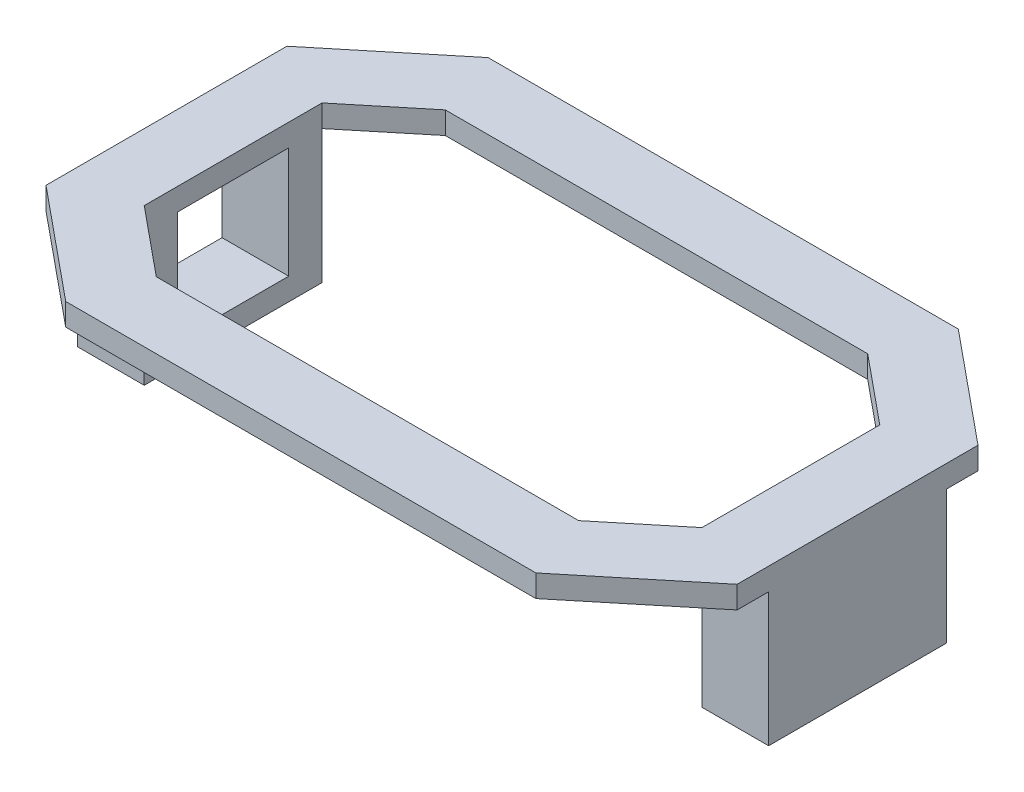
SolidWorks part; units mm, degrees
ref_plane "Front Plane" through (0, 0, 0) normal (0, 0, 1) x (1, 0, 0)
ref_plane "Top Plane" through (0, 0, 0) normal (0, 1, 0) x (1, 0, 0)
ref_plane "Right Plane" through (0, 0, 0) normal (1, 0, 0) x (0, 0, -1)
sketch "Sketch1" plane through (0, 0, 0) normal (0, 1, 0) x (1, 0, 0)
  line L0 (15, 0) -> (140.43, 0) construction
  line L1 (0, 0) -> (15, 0)
  line L2 (0, 0) -> (0, 40)
  line L3 (0, 40) -> (15, 40)
  line L4 (15, 0) -> (15, 40)
  line L5 (0, 0) -> (15, 40) construction
  line L6 (0, 40) -> (15, 0) construction
  line L7 (147.93, 0) -> (147.93, 40) construction
  line L8 (140.43, 0) -> (155.43, 0)
  line L9 (140.43, 0) -> (140.43, 40)
  line L10 (140.43, 40) -> (155.43, 40)
  line L11 (155.43, 0) -> (155.43, 40)
  line L12 (140.43, 0) -> (155.43, 40) construction
  line L13 (140.43, 40) -> (155.43, 0) construction
  line L14 (140.43, 20) -> (155.43, 20) construction
  line L15 (77.715, 0) -> (77.715, 21.3226) construction
  circle A0 centre (144.18, 5) radius 2
  circle A1 centre (151.68, 5) radius 2
  circle A2 centre (151.68, 35) radius 2
  circle A3 centre (144.18, 35) radius 2
  circle A4 centre (3.75, 35) radius 2
  circle A5 centre (11.25, 35) radius 2
  circle A6 centre (11.25, 5) radius 2
  circle A7 centre (3.75, 5) radius 2
  point P4 (7.5, 20)
  point P10 (147.93, 20)
  dimension "D6" = 4
  dimension "D1" = 40
  dimension "D2" = 15
  dimension "D3" = 125.43
  dimension "D4" = 40
  dimension "D5" = 15
  dimension "D7" = 3.75
  dimension "D8" = 5
extrude "Boss-Extrude1" add sketch "Sketch1" along normal blind 30
sketch "Sketch2" plane through (0, 30, 0) normal (0, 1, 0) x (1, 0, 0)
  line L0 (15, 20) -> (140.43, 20) construction
  line L1 (15, 0) -> (15, 40) construction
  line L2 (140.43, 40) -> (140.43, 0) construction
  line L3 (15, 40) -> (30.215, 52.5)
  line L4 (30.215, -12.5) -> (125.215, -12.5) construction
  line L5 (30.215, -12.5) -> (30.215, 52.5) construction
  line L6 (30.215, 52.5) -> (125.215, 52.5) construction
  line L7 (125.215, -12.5) -> (125.215, 52.5) construction
  line L8 (30.215, -12.5) -> (125.215, 52.5) construction
  line L9 (30.215, 52.5) -> (125.215, -12.5) construction
  line L10 (30.215, 52.5) -> (125.215, 52.5)
  line L11 (125.215, 52.5) -> (140.43, 40)
  line L12 (140.43, 40) -> (140.43, 0)
  line L13 (140.43, 0) -> (125.215, -12.5)
  line L14 (125.215, -12.5) -> (30.215, -12.5)
  line L15 (30.215, -12.5) -> (15, 0)
  line L16 (15, 0) -> (15, 40)
  line L17 (130.5865, -27.5) -> (24.8435, -27.5)
  line L18 (24.8435, -27.5) -> (0, -7.0897)
  line L19 (0, -7.0897) -> (0, 47.0897)
  line L20 (0, 47.0897) -> (24.8435, 67.5)
  line L21 (24.8435, 67.5) -> (130.5865, 67.5)
  line L22 (130.5865, 67.5) -> (155.43, 47.0897)
  line L23 (155.43, 47.0897) -> (155.43, -7.0897)
  line L24 (155.43, -7.0897) -> (130.5865, -27.5)
  point P6 (77.715, 20)
  dimension "D1" = 65
  dimension "D2" = 95
  dimension "D3" = 15
extrude "Boss-Extrude2" add sketch "Sketch2" along normal blind 5
sketch "Sketch3" plane through (15, 0, 0) normal (1, 0, 0) x (0, 0, -1)
  line L0 (52.5, 30) -> (32.5, 30) construction
  line L1 (-12.5, 30) -> (7.5, 30) construction
  line L3 (32.5, 30) -> (7.5, 30)
  line L4 (32.5, 30) -> (32.5, 5)
  line L5 (32.5, 5) -> (7.5, 5)
  line L6 (7.5, 30) -> (7.5, 5)
  line L7 (32.5, 30) -> (7.5, 5) construction
  line L8 (32.5, 5) -> (7.5, 30) construction
  point P9 (20, 17.5)
  dimension "D1" = 20
  dimension "D2" = 20
  dimension "D3" = 25
extrude "Cut-Extrude1" cut sketch "Sketch3" against normal blind 25
